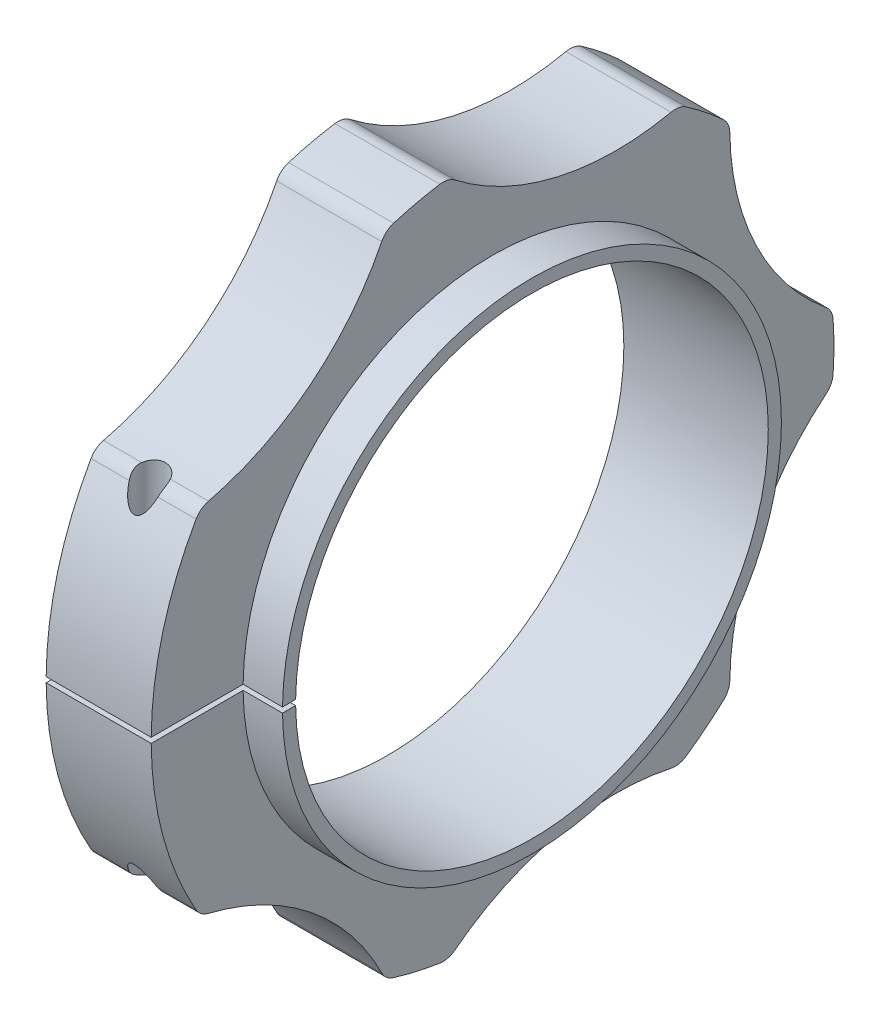
SolidWorks part; units mm, degrees
ref_plane "Alzado" through (0, 0, 0) normal (0, 0, 1) x (1, 0, 0)
ref_plane "Planta" through (0, 0, 0) normal (0, 1, 0) x (1, 0, 0)
ref_plane "Vista lateral" through (0, 0, 0) normal (1, 0, 0) x (0, 0, -1)
sketch "Croquis1" plane through (0, 0, 0) normal (1, 0, 0) x (0, 0, -1)
  line L0 (0, 0) -> (-26, 0) construction
  arc A0 (-22.245, 13.4595) -> (-22.245, -13.4595) centre (0, 0) ccw
  circle A1 centre (0, 0) radius 18
  arc A2 (-24.3926, 9) -> (-24.3926, -9) centre (-42.2532, 0) cw construction
  arc A3 (-8.1721, 24.6823) -> (-22.245, 13.4595) centre (-26.3444, 33.0349) cw
  arc A4 (14.2022, 21.7784) -> (-3.3465, 25.7837) centre (9.4022, 41.1938) cw
  arc A5 (25.8819, 2.4748) -> (18.072, 18.6923) centre (38.0688, 18.333) cw
  arc A6 (18.072, -18.6923) -> (25.8819, -2.4748) centre (38.0688, -18.333) cw
  arc A7 (-3.3465, -25.7837) -> (14.2022, -21.7784) centre (9.4022, -41.1938) cw
  arc A8 (-22.245, -13.4595) -> (-8.1721, -24.6823) centre (-26.3444, -33.0349) cw
  arc A9 (-8.1721, -24.6823) -> (-3.3465, -25.7837) centre (0, 0) ccw
  arc A10 (14.2022, -21.7784) -> (18.072, -18.6923) centre (0, 0) ccw
  arc A11 (25.8819, -2.4748) -> (25.8819, 2.4748) centre (0, 0) ccw
  arc A12 (18.072, 18.6923) -> (14.2022, 21.7784) centre (0, 0) ccw
  arc A13 (-3.3465, 25.7837) -> (-8.1721, 24.6823) centre (0, 0) ccw
  point P8 (-22.2532, 0)
  point P30 (0, 0)
  dimension "D1" = 52
  dimension "D2" = 36
  dimension "D5" = 20
  dimension "D4" = 18
  dimension "D3" = 7
extrude "Saliente-Extruir1" add sketch "Croquis1" along normal blind 8
sketch "Croquis2" plane through (8, 0, 0) normal (1, 0, 0) x (0, 0, -1)
  circle A0 centre (0, 0) radius 18 construction
  circle A1 centre (0, 0) radius 18
  circle A2 centre (0, 0) radius 19
  dimension "D1" = 1
extrude "Saliente-Extruir2" add sketch "Croquis2" along normal blind 3
sketch "Croquis3" plane through (0, 0, 0) normal (1, 0, 0) x (0, 0, -1)
  line L0 (0, 0) -> (-33, 0) construction
  line L1 (0, 0.2) -> (-33, 0.2)
  line L2 (0, -0.2) -> (-33, -0.2)
  line L3 (-33, 0.2) -> (-33, -0.2)
  line L4 (0, 0.2) -> (0, -0.2)
  dimension "D1" = 33
  dimension "D2" = 0.2
  dimension "D3" = 0.2
extrude "Cortar-Extruir2" cut sketch "Croquis3" against normal mid plane 33
fillet "Redondeo1" radius 1.5 12 edges at (4, -21.7784, -14.2022) (4, -18.6923, -18.072) (4, -2.4748, -25.8819) (4, 2.4748, -25.8819) (4, 18.6923, -18.072) (4, 21.7784, -14.2022) (4, 25.7837, 3.3465) (4, 24.6823, 8.1721) (4, 13.4595, 22.245) (4, -25.7837, 3.3465) (4, -24.6823, 8.1721) (4, -13.4595, 22.245)
sketch "Croquis4" plane through (0, 0.2, 0) normal (0, -1, 0) x (1, 0, 0)
  line L1 (4, 21.6342) -> (4, 22.5839) construction
  line L2 (0, 21.6342) -> (8, 21.6342) construction
  line L3 (8, 22.5839) -> (0, 22.5839) construction
  circle A0 centre (4, 22.1091) radius 1.1906
  point P12 (4, 22.1091)
  dimension "D1" = 2.3813
extrude "Cortar-Extruir3" cut sketch "Croquis4" against normal mid plane 33
